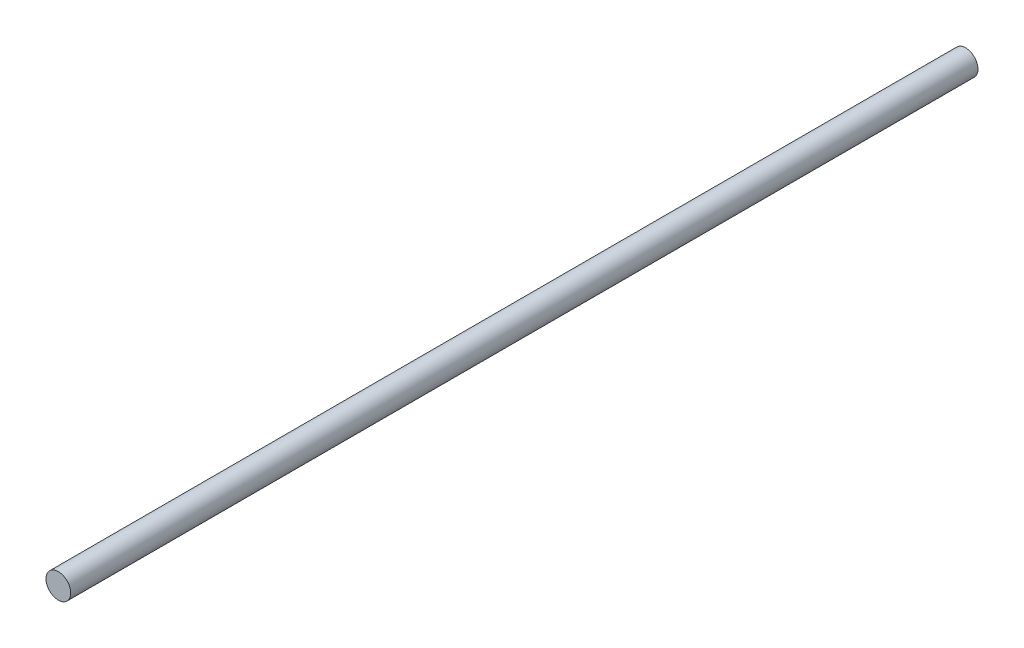
SolidWorks part; units mm, degrees
ref_plane "前视基准面" through (0, 0, 0) normal (0, 0, 1) x (1, 0, 0)
ref_plane "上视基准面" through (0, 0, 0) normal (0, 1, 0) x (1, 0, 0)
ref_plane "右视基准面" through (0, 0, 0) normal (1, 0, 0) x (0, 0, -1)
sketch "草图1" plane through (0, 0, 0) normal (0, 0, 1) x (1, 0, 0)
  circle A0 centre (0, 0) radius 3
extrude "凸台-拉伸1" add sketch "草图1" along normal blind 220
